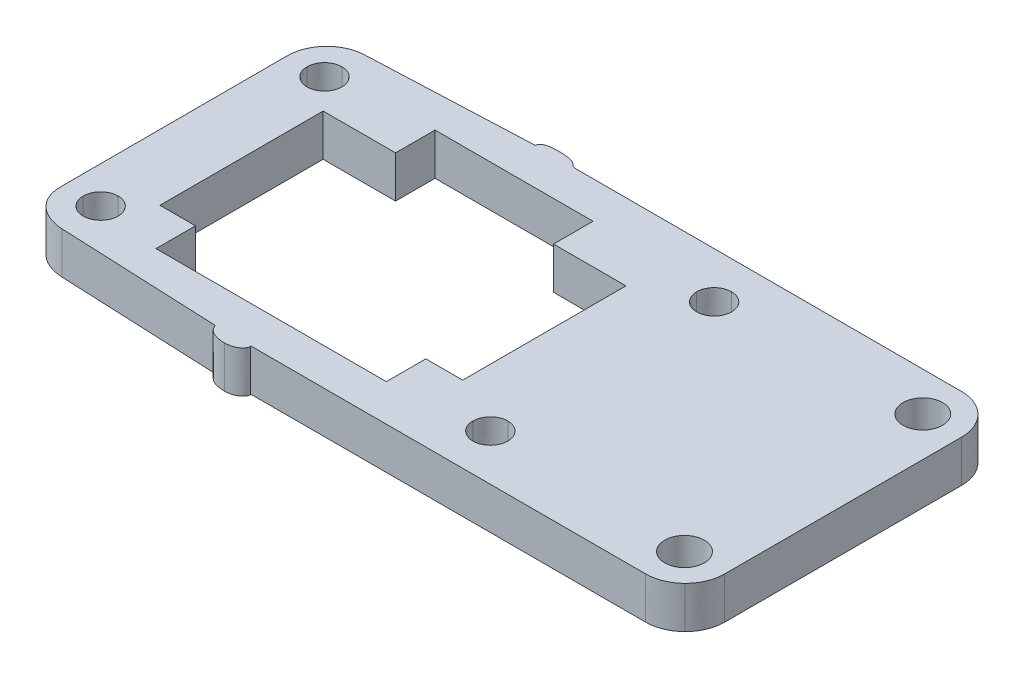
SolidWorks part; units mm, degrees
ref_plane "Front Plane" through (0, 0, 0) normal (0, 0, 1) x (1, 0, 0)
ref_plane "Top Plane" through (0, 0, 0) normal (0, 1, 0) x (1, 0, 0)
ref_plane "Right Plane" through (0, 0, 0) normal (1, 0, 0) x (0, 0, -1)
sketch "Sketch2" plane through (0, 0, 0) normal (0, 1, 0) x (1, 0, 0)
  line L558 (104.8605, 66.1087) -> (104.8105, 66.1087)
  line L559 (104.8105, 66.1087) -> (104.8105, 63.1087)
  line L560 (104.8105, 63.1087) -> (87.3105, 63.1087)
  line L561 (87.3105, 63.1087) -> (87.3105, 66.1087)
  line L562 (87.3105, 66.1087) -> (84.6105, 66.1087)
  line L563 (84.6105, 66.1087) -> (84.6105, 78.5086)
  line L564 (84.6105, 78.5086) -> (90.1105, 78.5086)
  line L565 (90.1105, 78.5086) -> (90.1105, 81.5086)
  line L566 (90.1105, 81.5086) -> (102.1106, 81.5086)
  line L567 (102.1106, 81.5086) -> (102.1106, 78.5086)
  line L568 (102.1106, 78.5086) -> (107.6105, 78.5086)
  line L569 (107.6105, 78.5086) -> (107.6105, 66.1087)
  line L570 (107.6105, 66.1087) -> (104.8605, 66.1087)
  line L571 (97.2812, 60.3087) -> (127.3105, 60.3087)
  line L572 (130.3105, 63.3087) -> (130.3105, 81.3086)
  line L573 (94.9178, 84.3086) -> (82.4534, 83.7762)
  line L574 (79.6105, 80.7804) -> (79.6246, 63.5445)
  line L575 (82.4534, 60.841) -> (94.6268, 60.3087)
  circle A0 centre (127.3105, 81.3586) radius 1.5001
  circle A1 centre (127.3105, 63.2587) radius 1.4999
  spline S277 degree 3 poles (81.0854, 63.8087) (81.0854, 63.0769) (81.6787, 62.4836) (82.4103, 62.4836) knots 0 0 0 0 0.2 0.2 0.2 0.2
  spline S278 degree 3 poles (82.4103, 62.4836) (83.1422, 62.4836) (83.7354, 63.0769) (83.7354, 63.8086) knots 0.2 0.2 0.2 0.2 0.4 0.4 0.4 0.4
  spline S279 degree 3 poles (83.7354, 63.8086) (83.7354, 64.5404) (83.1422, 65.1336) (82.4105, 65.1336) knots 0.4 0.4 0.4 0.4 0.6 0.6 0.6 0.6
  spline S280 degree 3 poles (82.4105, 65.1336) (81.6787, 65.1336) (81.0854, 64.5404) (81.0854, 63.8087) knots 0.6 0.6 0.6 0.6 1 1 1 1
  spline S281 degree 3 poles (81.0854, 80.8086) (81.0854, 80.0768) (81.6787, 79.4835) (82.4103, 79.4835) knots 0 0 0 0 0.2 0.2 0.2 0.2
  spline S282 degree 3 poles (82.4103, 79.4835) (83.1422, 79.4835) (83.7354, 80.0768) (83.7354, 80.8085) knots 0.2 0.2 0.2 0.2 0.4 0.4 0.4 0.4
  spline S283 degree 3 poles (83.7354, 80.8085) (83.7354, 81.5403) (83.1422, 82.1335) (82.4105, 82.1335) knots 0.4 0.4 0.4 0.4 0.6 0.6 0.6 0.6
  spline S284 degree 3 poles (82.4105, 82.1335) (81.6787, 82.1335) (81.0854, 81.5403) (81.0854, 80.8086) knots 0.6 0.6 0.6 0.6 1 1 1 1
  spline S285 degree 3 poles (94.6268, 60.3087) (94.6269, 60.3087) (94.7496, 59.5122) (96.1105, 59.5122) knots 0 0 0 0 0.058824 0.058824 0.058824 0.058824
  spline S286 degree 3 poles (96.1105, 59.5122) (97.2244, 59.5122) (97.4504, 60.3087) (97.2812, 60.3087) knots 0.058824 0.058824 0.058824 0.058824 0.117647 0.117647 0.117647 0.117647
  spline S287 degree 3 poles (127.3105, 60.3087) (128.1061, 60.3087) (128.8691, 60.6247) (129.4317, 61.1873) knots 0.176471 0.176471 0.176471 0.176471 0.235294 0.235294 0.235294 0.235294
  spline S288 degree 3 poles (129.4317, 61.1873) (129.9943, 61.7499) (130.3105, 62.513) (130.3105, 63.3087) knots 0.235294 0.235294 0.235294 0.235294 0.294118 0.294118 0.294118 0.294118
  spline S289 degree 3 poles (130.3105, 81.3086) (130.3105, 82.1042) (129.9943, 82.8673) (129.4317, 83.4299) knots 0.352941 0.352941 0.352941 0.352941 0.411765 0.411765 0.411765 0.411765
  spline S290 degree 3 poles (129.4317, 83.4299) (128.8691, 83.9925) (128.1061, 84.3086) (127.3105, 84.3086) knots 0.411765 0.411765 0.411765 0.411765 0.470588 0.470588 0.470588 0.470588
  spline S291 degree 2 poles (127.3105, 84.3086) (106.1437, 84.3086) (98.0308, 84.3086) knots 0.470588 0.470588 0.470588 0.529412 0.529412 0.529412
  spline S292 degree 3 poles (98.0308, 84.3086) (97.3832, 84.3086) (97.9635, 84.8125) (96.1105, 84.8125) knots 0.529412 0.529412 0.529412 0.529412 0.588235 0.588235 0.588235 0.588235
  spline S293 degree 2 poles (96.1105, 84.8125) (94.9984, 84.8125) (94.9178, 84.3086) knots 0.588235 0.588235 0.588235 0.647059 0.647059 0.647059
  spline S294 degree 3 poles (82.4534, 83.7762) (80.8598, 83.6927) (79.6105, 82.3762) (79.6105, 80.7804) knots 0.705882 0.705882 0.705882 0.705882 0.764706 0.764706 0.764706 0.764706
  spline S295 degree 3 poles (79.6246, 63.5445) (79.6246, 61.9487) (80.8598, 60.9245) (82.4534, 60.841) knots 0.823529 0.823529 0.823529 0.823529 0.882353 0.882353 0.882353 0.882353
  spline S304 degree 3 poles (110.6853, 63.8086) (110.6853, 63.0768) (111.2786, 62.4835) (112.0102, 62.4835) knots 0 0 0 0 0.2 0.2 0.2 0.2
  spline S305 degree 3 poles (112.0102, 62.4835) (112.7421, 62.4835) (113.3353, 63.0768) (113.3353, 63.8085) knots 0.2 0.2 0.2 0.2 0.4 0.4 0.4 0.4
  spline S306 degree 3 poles (113.3353, 63.8085) (113.3353, 64.5403) (112.7421, 65.1335) (112.0104, 65.1335) knots 0.4 0.4 0.4 0.4 0.6 0.6 0.6 0.6
  spline S307 degree 3 poles (112.0104, 65.1335) (111.2786, 65.1335) (110.6853, 64.5403) (110.6853, 63.8086) knots 0.6 0.6 0.6 0.6 1 1 1 1
  spline S308 degree 3 poles (110.6853, 80.8085) (110.6853, 80.0767) (111.2786, 79.4834) (112.0102, 79.4834) knots 0 0 0 0 0.2 0.2 0.2 0.2
  spline S309 degree 3 poles (112.0102, 79.4834) (112.7421, 79.4834) (113.3353, 80.0767) (113.3353, 80.8084) knots 0.2 0.2 0.2 0.2 0.4 0.4 0.4 0.4
  spline S310 degree 3 poles (113.3353, 80.8084) (113.3353, 81.5402) (112.7421, 82.1334) (112.0104, 82.1334) knots 0.4 0.4 0.4 0.4 0.6 0.6 0.6 0.6
  spline S311 degree 3 poles (112.0104, 82.1334) (111.2786, 82.1334) (110.6853, 81.5402) (110.6853, 80.8085) knots 0.6 0.6 0.6 0.6 1 1 1 1
extrude "Boss-Extrude1" add sketch "Sketch2" along normal blind 3.175
